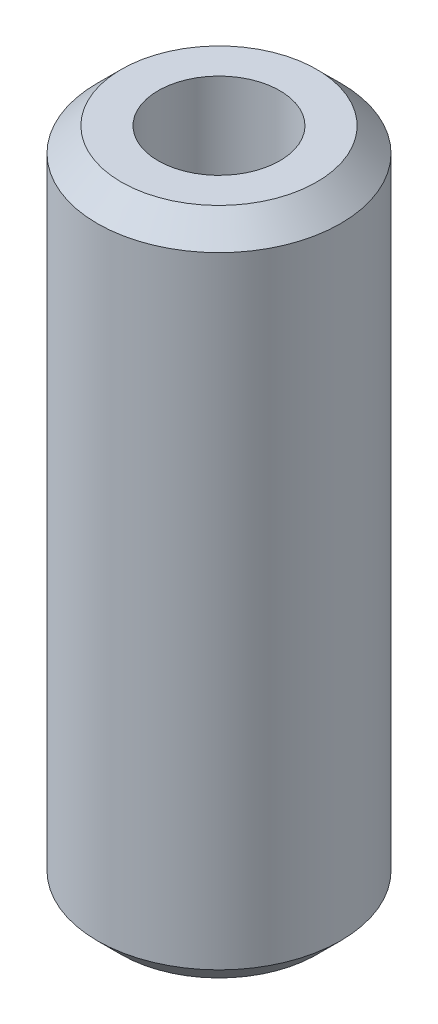
SolidWorks part; units mm, degrees
ref_plane "Front Plane" through (0, 0, 0) normal (0, 0, 1) x (1, 0, 0)
ref_plane "Top Plane" through (0, 0, 0) normal (0, 1, 0) x (1, 0, 0)
ref_plane "Right Plane" through (0, 0, 0) normal (1, 0, 0) x (0, 0, -1)
sketch "Sketch1" plane through (0, 0, 0) normal (0, 1, 0) x (1, 0, 0)
  circle A0 centre (0, 0) radius 6.35
  circle A1 centre (0, 0) radius 12.7
  dimension "D1" = 12.7
  dimension "D2" = 25.4
extrude "Boss-Extrude1" add sketch "Sketch1" along normal mid plane 69.85
chamfer "Chamfer1" distance 2.5 angle 45 2 edges at (0, -34.925, 12.7) (0, 34.925, 12.7)
scale "Scale1" scale about centroid uniform scaling yes scale factor 0.51948
